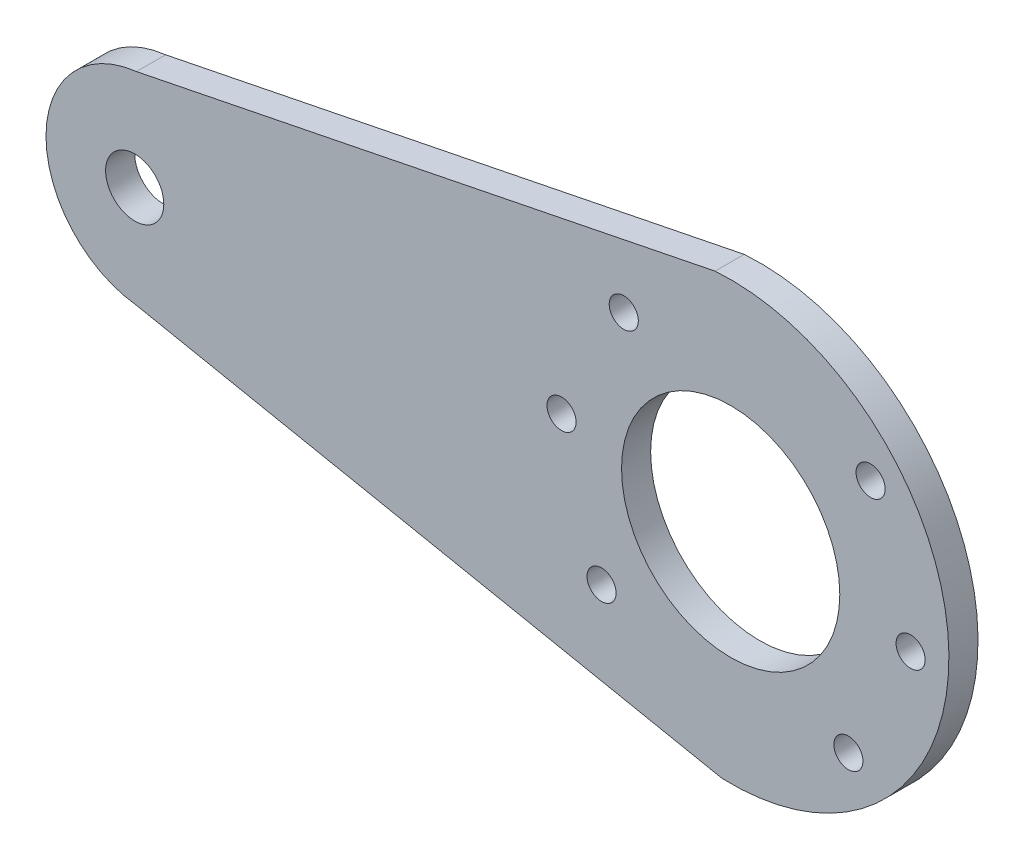
SolidWorks part; units mm, degrees
ref_plane "Спереди" through (0, 0, 0) normal (0, 0, 1) x (1, 0, 0)
ref_plane "Сверху" through (0, 0, 0) normal (0, 1, 0) x (1, 0, 0)
ref_plane "Справа" through (0, 0, 0) normal (1, 0, 0) x (0, 0, -1)
sketch "Эскиз1" plane through (0, 0, 0) normal (0, 0, 1) x (1, 0, 0)
  line L0 (0, 0) -> (-76.7265, 0) construction
  line L1 (-81.6768, 13.912) -> (-2.138, 29.9237)
  line L2 (-81.7023, -13.9091) -> (-1.2006, -29.976)
  circle A0 centre (0, 0) radius 15
  arc A1 (-1.2006, -29.976) -> (-2.138, 29.9237) centre (0, 0) ccw
  arc A2 (-81.6768, 13.912) -> (-81.7023, -13.9091) centre (-80.1094, 0) ccw
  circle A4 centre (-81.9176, 0) radius 4
extrude "Вытянуть1" add sketch "Эскиз1" along normal blind 4 from offset 2
sketch "Эскиз2" plane through (0, 0, 2) normal (0, 0, 1) x (1, 0, 0)
  circle A0 centre (-17.747, -15.2052) radius 2
  circle A1 centre (-23.2474, 2.391) radius 2
  circle A2 centre (-14.6943, 18.7227) radius 2
  circle A4 centre (19.2336, 15.6699) radius 2
  circle A5 centre (24.734, -1.9263) radius 2
  circle A6 centre (16.1809, -18.258) radius 2
  circle A8 centre (-1.4153, -23.7583) radius 2 [skipped]
  circle A9 centre (2.9019, 24.223) radius 2 [skipped]
extrude "Вырез-Вытянуть1" cut sketch "Эскиз2" against normal through all
